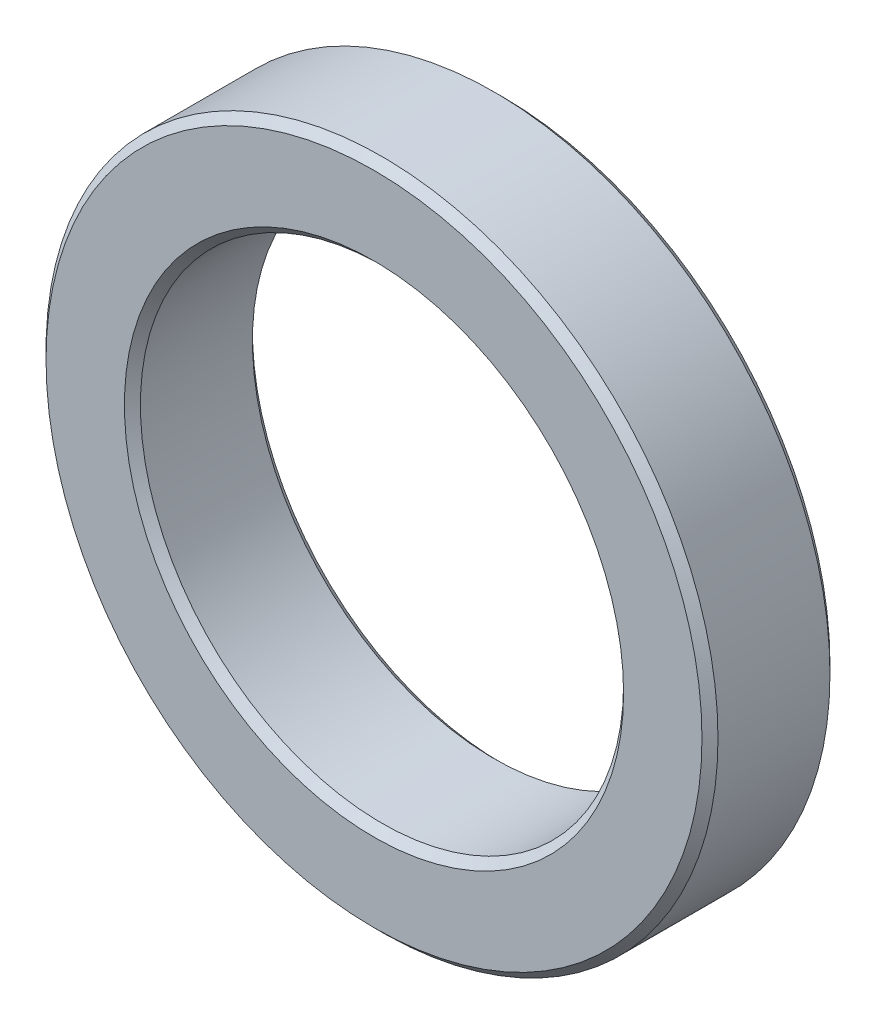
SolidWorks part; units mm, degrees
material "镀铬不锈钢"
ref_plane "前视基准面" through (0, 0, 0) normal (0, 0, 1) x (1, 0, 0)
ref_plane "上视基准面" through (0, 0, 0) normal (0, 1, 0) x (1, 0, 0)
ref_plane "右视基准面" through (0, 0, 0) normal (1, 0, 0) x (0, 0, -1)
sketch "草图1" plane through (0, 0, 0) normal (0, 0, 1) x (1, 0, 0)
  circle A0 centre (0, 0) radius 21
  circle A1 centre (0, 0) radius 15.1
  dimension "D1" = 30.2
  dimension "D2" = 42
extrude "凸台-拉伸1" add sketch "草图1" along normal mid plane 8
chamfer "倒角1" distance 0.5 angle 45 4 edges at (15.1, 0, -4) (15.1, 0, 4) (21, 0, -4) (21, 0, 4)
equation "\"24。6\"=4.7186"
